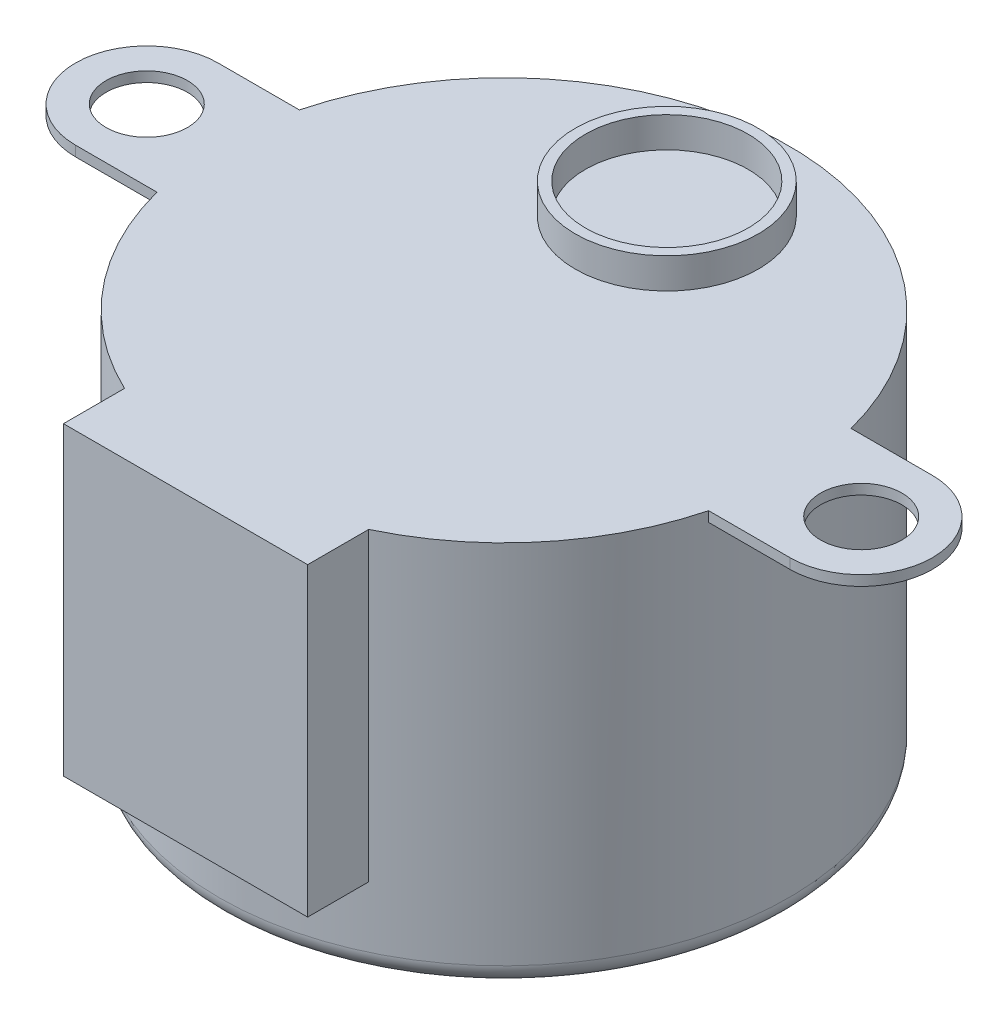
SolidWorks part; units mm, degrees
ref_plane "前视基准面" through (0, 0, 0) normal (0, 0, 1) x (1, 0, 0)
ref_plane "上视基准面" through (0, 0, 0) normal (0, 1, 0) x (1, 0, 0)
ref_plane "右视基准面" through (0, 0, 0) normal (1, 0, 0) x (0, 0, -1)
other "Configuration Table"
sketch "草图1" plane through (0, 0, 0) normal (0, 1, 0) x (1, 0, 0)
  circle A0 centre (0, 0) radius 14
  dimension "D1" = 28
extrude "凸台-拉伸1" add sketch "草图1" along normal blind 19
sketch "草图2" plane through (0, 19, 0) normal (0, 1, 0) x (1, 0, 0)
  circle A0 centre (0, 8) radius 4.5
  dimension "D1" = 9
  dimension "D2" = 8
extrude "凸台-拉伸2" add sketch "草图2" along normal blind 1.5
sketch "草图3" plane through (0, 20.5, 0) normal (0, 1, 0) x (1, 0, 0)
  circle A0 centre (0, 8) radius 4
  circle A1 centre (0, 8) radius 4.5 construction
  dimension "D1" = 8
extrude "切除-拉伸1" cut sketch "草图3" against normal blind 1.5
sketch "草图4" plane through (0, 19, 0) normal (0, 1, 0) x (1, 0, 0)
  line L0 (0, -14) -> (0, 14) construction
  line L1 (-13.5554, 3.5) -> (-17.5554, 3.5)
  line L2 (14, 0) -> (-14, 0) construction
  line L3 (-13.5554, -3.5) -> (-17.5554, -3.5)
  line L4 (13.5554, 3.5) -> (17.5554, 3.5)
  line L5 (13.5554, -3.5) -> (17.5554, -3.5)
  circle A0 centre (0, 0) radius 14 construction
  arc A1 (-17.5554, 3.5) -> (-17.5554, -3.5) centre (-17.5554, 0) ccw
  arc A2 (-13.5554, 3.5) -> (-13.5554, -3.5) centre (0, 0) ccw
  arc A3 (13.5554, 3.5) -> (13.5554, -3.5) centre (0, 0) cw
  arc A4 (17.5554, 3.5) -> (17.5554, -3.5) centre (17.5554, 0) cw
  dimension "D1" = 4
  dimension "D2" = 7
extrude "凸台-拉伸3" add sketch "草图4" against normal blind 0.5
sketch "草图5" plane through (0, 19, 0) normal (0, 1, 0) x (1, 0, 0)
  line L0 (0, -14) -> (0, 14) construction
  circle A0 centre (-17.5554, 0) radius 2
  arc A1 (-17.5554, 3.5) -> (-17.5554, -3.5) centre (-17.5554, 0) ccw construction
  arc A2 (-13.5554, -3.5) -> (13.5554, -3.5) centre (0, 0) ccw construction
  arc A3 (13.5554, 3.5) -> (-13.5554, 3.5) centre (0, 0) ccw construction
  circle A4 centre (17.5554, 0) radius 2
  dimension "D1" = 4
extrude "切除-拉伸2" cut sketch "草图5" against normal through all
sketch "草图6" plane through (0, 19, 0) normal (0, 1, 0) x (1, 0, 0)
  line L0 (0, -14) -> (0, 14) construction
  line L1 (-6, -12.6491) -> (-6, -15.6491)
  line L2 (6, -12.6491) -> (6, -15.6491)
  line L3 (-6, -15.6491) -> (6, -15.6491)
  arc A0 (-13.5554, -3.5) -> (13.5554, -3.5) centre (0, 0) ccw construction
  arc A1 (13.5554, 3.5) -> (-13.5554, 3.5) centre (0, 0) ccw construction
  arc A2 (6, -12.6491) -> (-6, -12.6491) centre (0, 0) cw
  dimension "D1" = 12
  dimension "D2" = 3
extrude "凸台-拉伸4" add sketch "草图6" against normal blind 15
fillet "圆角1" radius 1 1 edges at (0, 0, 14)
sketch "草图7" plane through (0, 0, 0) normal (0, -1, 0) x (1, 0, 0)
  line L0 (0, 9) -> (0, -9) construction
  line L1 (-9, 0) -> (9, 0) construction
  line L2 (0, 0) -> (3.4442, 8.3149) construction
  line L3 (0.6978, 4.9511) -> (2.9769, 8.4934)
  line L4 (3.0075, 3.9944) -> (3.9008, 8.1107)
  circle A0 centre (0, 0) radius 5 construction
  circle A1 centre (0, 0) radius 9 construction
  arc A2 (0.6978, 4.9511) -> (3.0075, 3.9944) centre (0, 0) cw
  arc A3 (2.9769, 8.4934) -> (3.9008, 8.1107) centre (0, 0) cw
  dimension "D1" = 10
  dimension "D2" = 18
  dimension "D4" = 2.5
  dimension "D3" = 22.5
  dimension "D5" = 1
extrude "切除-拉伸3" cut sketch "草图7" against normal blind 1
fillet "圆角2" radius 0.3 2 edges at (3.9008, 0.5, 8.1107) (2.9769, 0.5, 8.4934)
pattern_circular "阵列(圆周)1" count 8 every 45 about axis through (-0.034, 0, -0.0821) along (0, 1, 0) of "圆角2", "切除-拉伸3"
